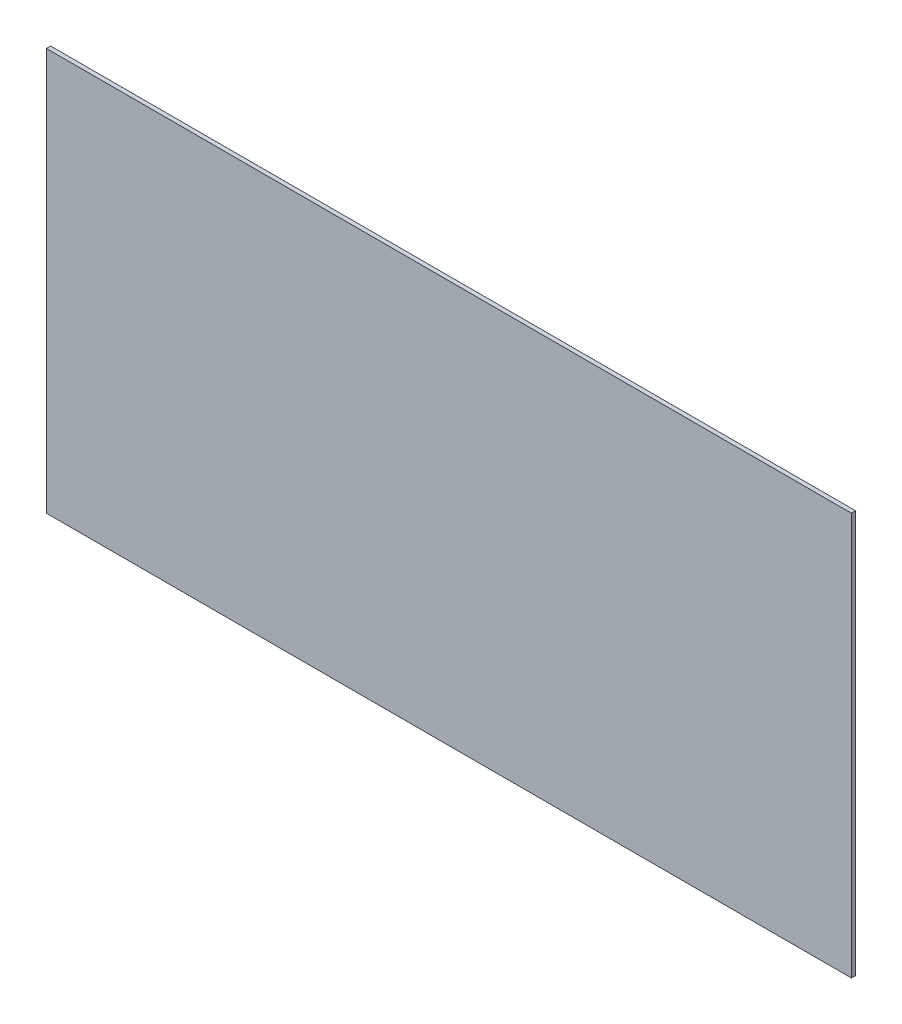
SolidWorks part; units mm, degrees
ref_plane "Front Plane" through (0, 0, 0) normal (0, 0, 1) x (1, 0, 0)
ref_plane "Top Plane" through (0, 0, 0) normal (0, 1, 0) x (1, 0, 0)
ref_plane "Right Plane" through (0, 0, 0) normal (1, 0, 0) x (0, 0, -1)
sketch "Sketch1" plane through (0, 0, 0) normal (0, 0, 1) x (1, 0, 0)
  line L1 (-304.8, -152.4) -> (304.8, -152.4)
  line L2 (-304.8, -152.4) -> (-304.8, 152.4)
  line L3 (-304.8, 152.4) -> (304.8, 152.4)
  line L4 (304.8, -152.4) -> (304.8, 152.4)
  line L5 (0, 152.4) -> (0, -152.4) construction
  line L6 (-304.8, 0) -> (304.8, 0) construction
  point P0 (0, 0)
  point P4 (-213.36, 0)
  point P5 (213.36, 0)
  point P6 (0, 106.68)
  point P7 (0, -106.68)
  dimension "Length" = 609.6
  dimension "Width" = 304.8
  dimension "Break" = 91.44
  dimension "D2" = 91.44
  dimension "D1" = 45.72
  dimension "D3" = 45.72
sketch "Sketch2" plane through (0, 0, 0) normal (1, 0, 0) x (0, 0, -1)
  line L0 (-1.5875, -152.4) -> (1.5875, -152.4)
  dimension "Thickness" = 3.175
sketch "Sketch3" plane through (0, 0, 0) normal (0, 0, 1) x (1, 0, 0)
  line L0 (-304.8, -152.4) -> (-304.8, 152.4) construction
  line L1 (-304.8, -152.4) -> (304.8, -152.4) construction
  line L2 (304.8, -152.4) -> (304.8, 152.4) construction
  line L3 (-304.8, 152.4) -> (304.8, 152.4) construction
  line L4 (-304.8, -152.4) -> (-304.8, 152.4)
  line L5 (-304.8, -152.4) -> (304.8, -152.4)
  line L6 (304.8, -152.4) -> (304.8, 152.4)
  line L7 (-304.8, 152.4) -> (304.8, 152.4)
extrude "Boss-Extrude1" add sketch "Sketch3" along normal mid plane 3.175
equation "\"D1@Boss-Extrude1\"=\"thickness@sketch2\""
equation "\"Break@Sketch1\" = \"Length@Sketch1\" * 0.15"
equation "\"D2@Sketch1\" = \"Break@Sketch1\""
equation "\"D1@Sketch1\"=\"Width@Sketch1\"*0.15"
equation "\"D3@Sketch1\"=\"D1@Sketch1\""
